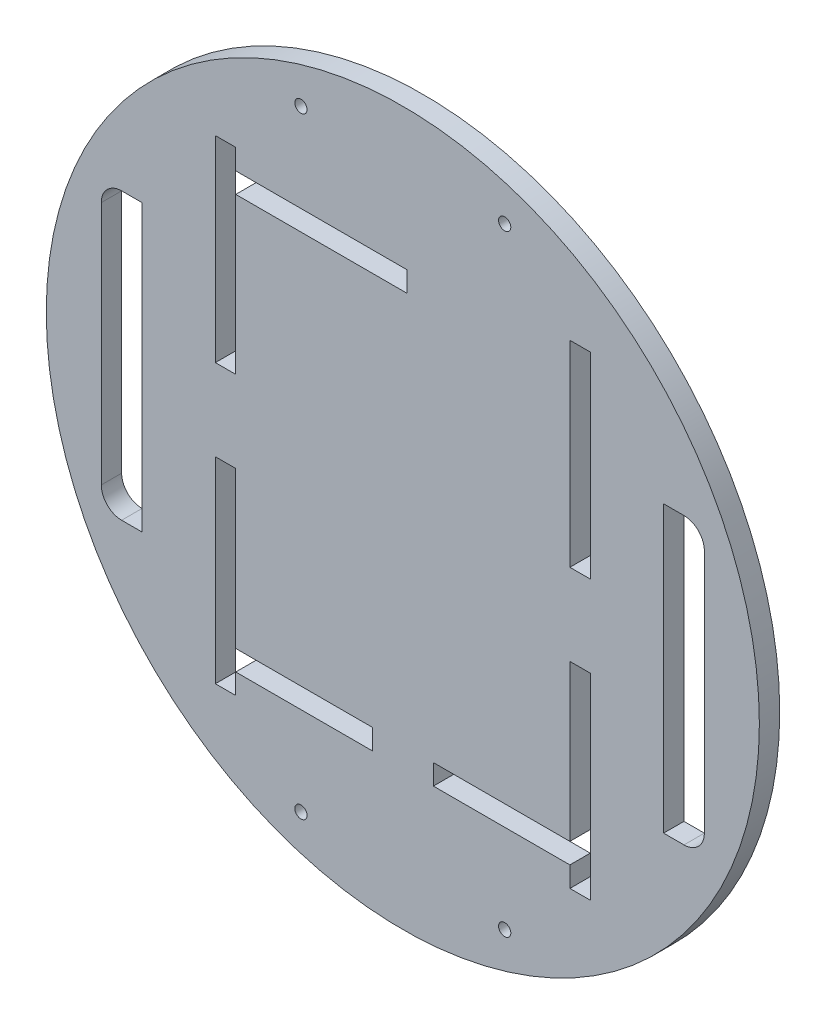
SolidWorks part; units mm, degrees
ref_plane "前基準面" through (0, 0, 0) normal (0, 0, 1) x (1, 0, 0)
ref_plane "上基準面" through (0, 0, 0) normal (0, 1, 0) x (1, 0, 0)
ref_plane "右基準面" through (0, 0, 0) normal (1, 0, 0) x (0, 0, -1)
sketch "草圖1" plane through (0, 0, 0) normal (0, 0, 1) x (1, 0, 0)
  circle A0 centre (0, 0) radius 87.5
  point P0 (0, 0)
  dimension "D7" = 175
extrude "填料-伸長1" add sketch "草圖1" along normal blind 5
sketch "草圖2" plane through (0, 0, 5) normal (0, 0, 1) x (1, 0, 0)
  line L0 (0, 109.0983) -> (0, -103.3143) construction
  line L1 (-118.0673, 0) -> (130.5826, 0) construction
  circle A0 centre (-25, 75) radius 1.5
  circle A1 centre (-25, -75) radius 1.5
  circle A2 centre (25, 75) radius 1.5
  circle A3 centre (25, -75) radius 1.5
  dimension "D1" = 3
  dimension "D2" = 75
  dimension "D3" = 25
sketch "草圖3" plane through (0, 0, 5) normal (0, 0, 1) x (1, 0, 0)
  line L0 (-64, 35) -> (-64, -35)
  line L1 (-74, 30) -> (-74, -30)
  line L2 (-64, 35) -> (-69, 35)
  line L3 (-64, -35) -> (-69, -35)
  line L4 (0, 127.9588) -> (0, -114.3515) construction
  line L5 (64, -35) -> (69, -35)
  line L6 (64, 35) -> (69, 35)
  line L7 (74, 30) -> (74, -30)
  line L8 (64, 35) -> (64, -35)
  arc A0 (-69, 35) -> (-74, 30) centre (-69, 30) ccw
  arc A1 (-69, -35) -> (-74, -30) centre (-69, -30) cw
  arc A2 (69, -35) -> (74, -30) centre (69, -30) ccw
  arc A3 (69, 35) -> (74, 30) centre (69, 30) cw
  dimension "D1" = 64
  dimension "D2" = 70
  dimension "D3" = 60
  dimension "D4" = 35
  dimension "D5" = 10
  dimension "D6" = 30
  dimension "D7" = 5
  dimension "D8" = 5
extrude "除料-伸長1" cut sketch "草圖3" against normal through all contours A1 L3 L0 L2 A0 L1 | L8 L5 A2 L7 A3 L6
extrude "除料-伸長2" cut sketch "草圖2" against normal through all
sketch "草圖4" plane through (0, 0, 5) normal (0, 0, 1) x (1, 0, 0)
  line L0 (0, 97.2889) -> (0, -101.2413) construction
  line L1 (46, -10) -> (41, -10)
  line L2 (46, 58.25) -> (46, 10)
  line L3 (-41, 58.25) -> (-41, 10)
  line L4 (41, -58.25) -> (46, -58.25)
  line L5 (41, 58.25) -> (41, 10)
  line L6 (41, 58.25) -> (46, 58.25)
  line L7 (-41, 58.25) -> (-46, 58.25)
  line L8 (-41, 58.25) -> (-41, 10)
  line L9 (-41, -58.25) -> (-46, -58.25)
  line L10 (-46, 58.25) -> (-46, 10)
  line L11 (41, 58.25) -> (41, 10)
  line L12 (-46, -10) -> (-41, -10)
  line L14 (-46, 10) -> (-41, 10)
  line L16 (46, 10) -> (41, 10)
  line L17 (-41, -10) -> (-41, -58.25)
  line L18 (-41, -10) -> (-41, -58.25)
  line L19 (-46, -10) -> (-46, -58.25)
  line L20 (41, -10) -> (41, -58.25)
  line L21 (41, -10) -> (41, -58.25)
  line L22 (46, -10) -> (46, -58.25)
  dimension "D1" = 41
  dimension "D2" = 116.5
  dimension "D3" = 58.25
  dimension "D4" = 5
  dimension "D5" = 20
  dimension "D6" = 10
extrude "除料-伸長4" cut sketch "草圖4" against normal through all contours L7 L10 L9 L3 | L6 L5 L4 L2 | L12 L19 L9 L17 | L22 L1 L20 L4
sketch "草圖5" plane through (0, 0, 5) normal (0, 0, 1) x (1, 0, 0)
  line L0 (-41, 58.25) -> (-41, 10) construction
  line L1 (-41, 48.25) -> (1, 48.25)
  line L2 (-41, 48.25) -> (-41, 53.25)
  line L3 (-41, 53.25) -> (1, 53.25)
  line L4 (1, 48.25) -> (1, 53.25)
  line L6 (-41, 58.25) -> (-46, 58.25) construction
  line L7 (41, 58.25) -> (41, 10) construction
  line L8 (-41, -48.25) -> (-7.5, -48.25)
  line L9 (-41, -48.25) -> (-41, -53.25)
  line L10 (-41, -53.25) -> (-7.5, -53.25)
  line L11 (41, -48.25) -> (41, -53.25)
  line L12 (-41, -58.25) -> (-46, -58.25) construction
  line L13 (7.5, -48.25) -> (41, -48.25)
  line L15 (-7.5, -53.25) -> (-7.5, -48.25)
  line L17 (7.5, -53.25) -> (7.5, -48.25)
  line L18 (7.5, -53.25) -> (41, -53.25)
  point P6 (-43.5, 58.25)
  dimension "D1" = 5
  dimension "D2" = 42
  dimension "D3" = 5
  dimension "D4" = 5
  dimension "D5" = 5
  dimension "D6" = 15
  dimension "D7" = 33.5
extrude "除料-伸長7" cut sketch "草圖5" against normal through all
